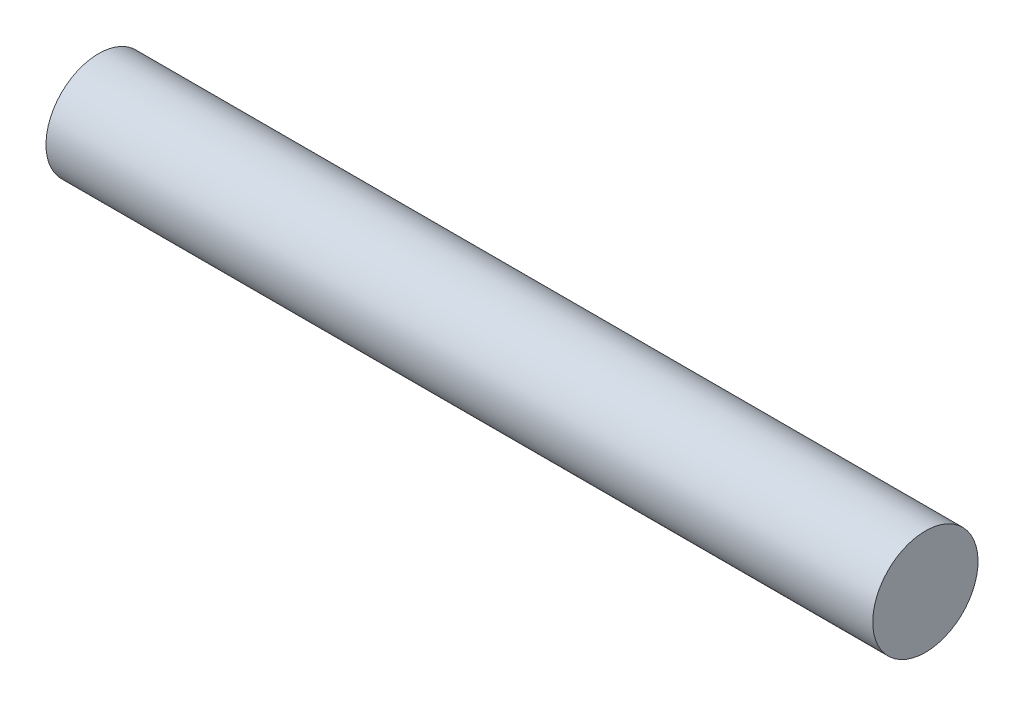
SolidWorks part; units mm, degrees
ref_plane "Front Plane" through (0, 0, 0) normal (0, 0, 1) x (1, 0, 0)
ref_plane "Top Plane" through (0, 0, 0) normal (0, 1, 0) x (1, 0, 0)
ref_plane "Right Plane" through (0, 0, 0) normal (1, 0, 0) x (0, 0, -1)
sketch "Sketch1" plane through (0, 0, 0) normal (1, 0, 0) x (0, 0, -1)
  circle A0 centre (0, 0) radius 3.57
  dimension "D1" = 7.14
extrude "Boss-Extrude1" add sketch "Sketch1" along normal up to surface (56.077 mm away)
